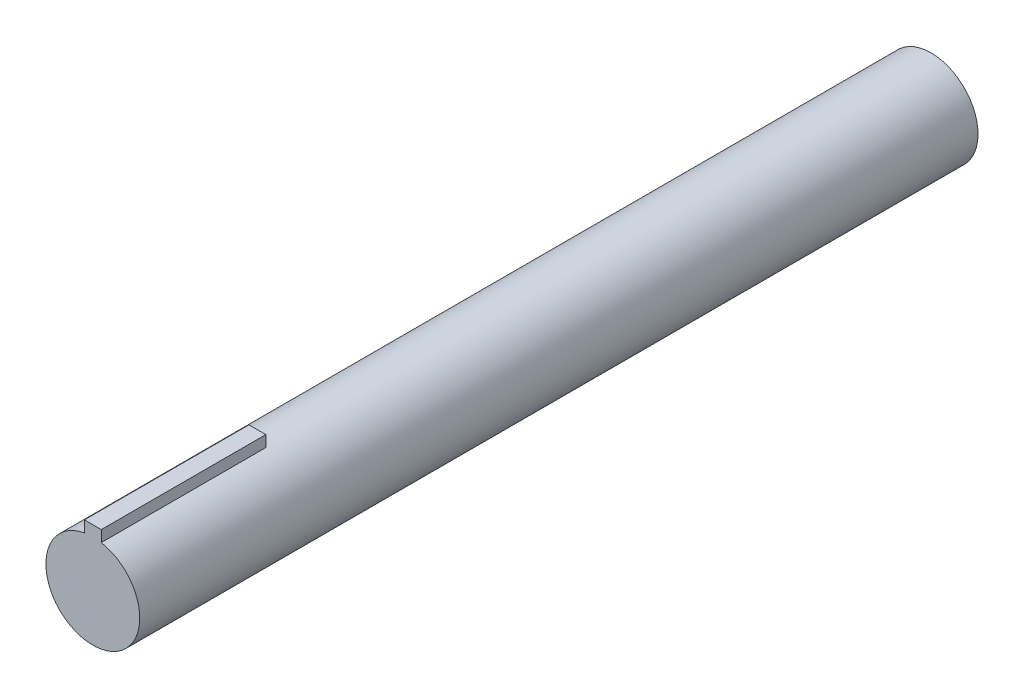
SolidWorks part; units mm, degrees
ref_plane "Alzado" through (0, 0, 0) normal (0, 0, 1) x (1, 0, 0)
ref_plane "Planta" through (0, 0, 0) normal (0, 1, 0) x (1, 0, 0)
ref_plane "Vista lateral" through (0, 0, 0) normal (1, 0, 0) x (0, 0, -1)
sketch "Croquis1" plane through (0, 0, 0) normal (0, 0, 1) x (1, 0, 0)
  line L0 (-53.0995, 8.0105) -> (-53.0995, 10.5105) construction
  line L3 (-53.5495, 10.4697) -> (-53.5495, 11.0697)
  line L4 (-53.5495, 11.0697) -> (-52.6495, 11.0697)
  line L5 (-52.6495, 10.4697) -> (-52.6495, 11.0697)
  arc A0 (-53.5495, 10.4697) -> (-52.6495, 10.4697) centre (-53.0995, 8.0105) ccw
  dimension "D1" = 5
  dimension "D2" = 0.9
  dimension "D3" = 0.6
extrude "Saliente-Extruir1" add sketch "Croquis1" along normal blind 8.77
sketch "Croquis2" plane through (0, 0, 0) normal (0, 0, -1) x (-1, 0, 0)
  circle A0 centre (53.0995, 8.0105) radius 2.5
extrude "Saliente-Extruir2" add sketch "Croquis2" along normal blind 25.9
sketch "Croquis3" plane through (0, 0, -25.9) normal (0, 0, -1) x (-1, 0, 0)
  circle A1 centre (53.0995, 8.0105) radius 2.5
extrude "Saliente-Extruir6" add sketch "Croquis3" along normal blind 10
sketch "Croquis8" plane through (0, 0, -35.9) normal (0, 0, -1) x (-1, 0, 0)
  line L0 (52.6495, 6.1514) -> (52.6495, 5.5514)
  line L1 (53.5495, 6.1514) -> (53.5495, 5.5514)
  line L2 (52.6495, 6.1514) -> (53.5495, 6.1514)
  circle A0 centre (53.0995, 8.0105) radius 2.5 construction
  arc A1 (52.6495, 5.5514) -> (53.5495, 5.5514) centre (53.0995, 8.0105) ccw
  dimension "D1" = 0.6
extrude "Cortar-Extruir1" cut sketch "Croquis8" against normal blind 10
